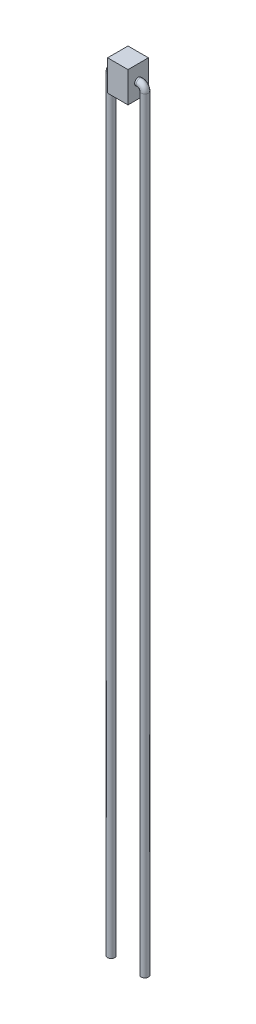
SolidWorks part; units mm, degrees
ref_plane "Front Plane" through (0, 0, 0) normal (0, 0, 1) x (1, 0, 0)
ref_plane "Top Plane" through (0, 0, 0) normal (0, 1, 0) x (1, 0, 0)
ref_plane "Right Plane" through (0, 0, 0) normal (1, 0, 0) x (0, 0, -1)
sketch "Sketch1" plane through (0, 0, 0) normal (0, 1, 0) x (1, 0, 0)
  line L1 (-1, -1) -> (1, -1)
  line L2 (-1, -1) -> (-1, 1)
  line L3 (-1, 1) -> (1, 1)
  line L4 (1, -1) -> (1, 1)
  line L5 (-1, -1) -> (1, 1) construction
  line L6 (-1, 1) -> (1, -1) construction
  point P0 (0, 0)
  dimension "D1" = 2
  dimension "D2" = 2
extrude "Boss-Extrude1" add sketch "Sketch1" along normal blind 3
sketch "Sketch2" plane through (0, 0, -1) normal (0, 0, -1) x (-1, 0, 0)
  line L0 (1, 3) -> (1, 0) construction
  circle A0 centre (0.45, 1.5005) radius 0.5
  dimension "D1" = 1
  dimension "D2" = 0.55
extrude "Cut-Extrude1" cut sketch "Sketch2" against normal blind 0.01
sketch "Sketch3" plane through (-1, 0, 0) normal (-1, 0, 0) x (0, 0, 1)
  line L0 (1, 3) -> (1, 0) construction
  line L1 (-1, 3) -> (1, 3) construction
  circle A0 centre (0, 1.5) radius 0.35
  point P3 (0, 1.5)
  dimension "D1" = 0.7
  dimension "D2" = 1
  dimension "D3" = 1.5
ref_plane "Plane1" through (-1, 1.5, 0) normal (0, 0, 1) x (1, 0, 0)
sketch "Sketch8" plane through (-1, 1.5, 0) normal (0, 0, 1) x (1, 0, 0)
  line L0 (0, 0) -> (-0.1528, 0)
  line L1 (-0.6528, -0.5) -> (-0.6528, -75.5)
  arc A0 (-0.1528, 0) -> (-0.6528, -0.5) centre (-0.1528, -0.5) ccw
  point P0 (0, 0)
  dimension "D3" = 0.5
  dimension "D1" = 75
sweep "Sweep1" add profiles "Sketch3" path "Sketch8"
mirror "Mirror1" about plane through (0, 0, 0) normal (1, 0, 0) of "Sweep1"
